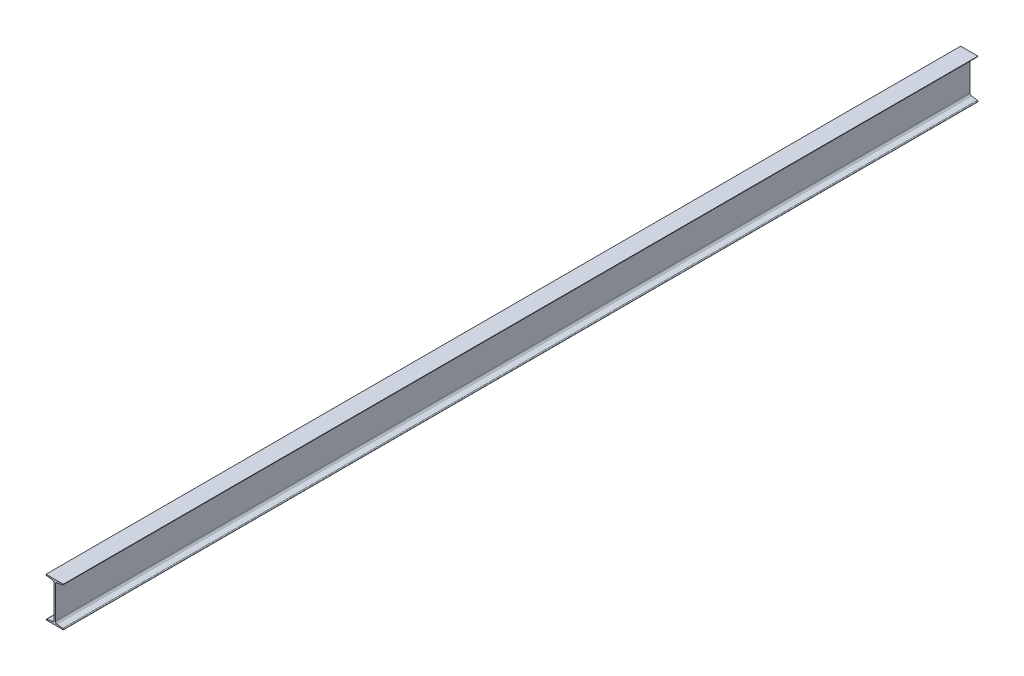
SolidWorks part; units mm, degrees
ref_plane "Front Plane" through (0, 0, 0) normal (0, 0, 1) x (1, 0, 0)
ref_plane "Top Plane" through (0, 0, 0) normal (0, 1, 0) x (1, 0, 0)
ref_plane "Right Plane" through (0, 0, 0) normal (1, 0, 0) x (0, 0, -1)
other "Configuration Table"
sketch "Sketch1" plane through (0, 0, 0) normal (0, 0, 1) x (1, 0, 0)
  line L0 (-66.675, -152.4) -> (-66.675, -152.0363)
  line L1 (-60.7319, -145.0211) -> (-17.7282, -137.8556)
  line L2 (-5.842, -123.825) -> (-5.842, 123.825)
  line L3 (-17.7282, 137.8556) -> (-60.7319, 145.0211)
  line L4 (-66.675, 152.0363) -> (-66.675, 152.4)
  line L5 (-66.675, 152.4) -> (66.675, 152.4)
  line L6 (66.675, 152.4) -> (66.675, 152.0363)
  line L7 (60.7319, 145.0211) -> (17.7282, 137.8556)
  line L8 (5.842, 123.825) -> (5.842, -123.825)
  line L9 (17.7282, -137.8556) -> (60.7319, -145.0211)
  line L10 (66.675, -152.0363) -> (66.675, -152.4)
  line L11 (66.675, -152.4) -> (-66.675, -152.4)
  line L14 (-5.842, 0) -> (5.842, 0) construction
  arc A0 (-17.7282, -137.8556) -> (-5.842, -123.825) centre (-20.066, -123.825) ccw
  arc A1 (-5.842, 123.825) -> (-17.7282, 137.8556) centre (-20.066, 123.825) ccw
  arc A2 (17.7282, 137.8556) -> (5.842, 123.825) centre (20.066, 123.825) ccw
  arc A3 (5.842, -123.825) -> (17.7282, -137.8556) centre (20.066, -123.825) ccw
  arc A4 (60.7319, 145.0211) -> (66.675, 152.0363) centre (59.563, 152.0363) ccw
  arc A5 (-60.7319, 145.0211) -> (-66.675, 152.0363) centre (-59.563, 152.0363) cw
  arc A6 (60.7319, -145.0211) -> (66.675, -152.0363) centre (59.563, -152.0363) cw
  arc A7 (-60.7319, -145.0211) -> (-66.675, -152.0363) centre (-59.563, -152.0363) ccw
  point P30 (0, 152.4)
  point P31 (0, -152.4)
  dimension "D7" = 9.46
  dimension "RI" = 14.224
  dimension "RA" = 7.112
  dimension "BF" = 133.35
  dimension "D6" = 9.46
  dimension "DEPTH" = 304.8
  dimension "TW" = 11.684
  dimension "D1" = 247.65
extrude "Extrude1" add sketch "Sketch1" along normal blind 7050
ref_point "Point1"
ref_point "Point2"
ref_point "Point3"
